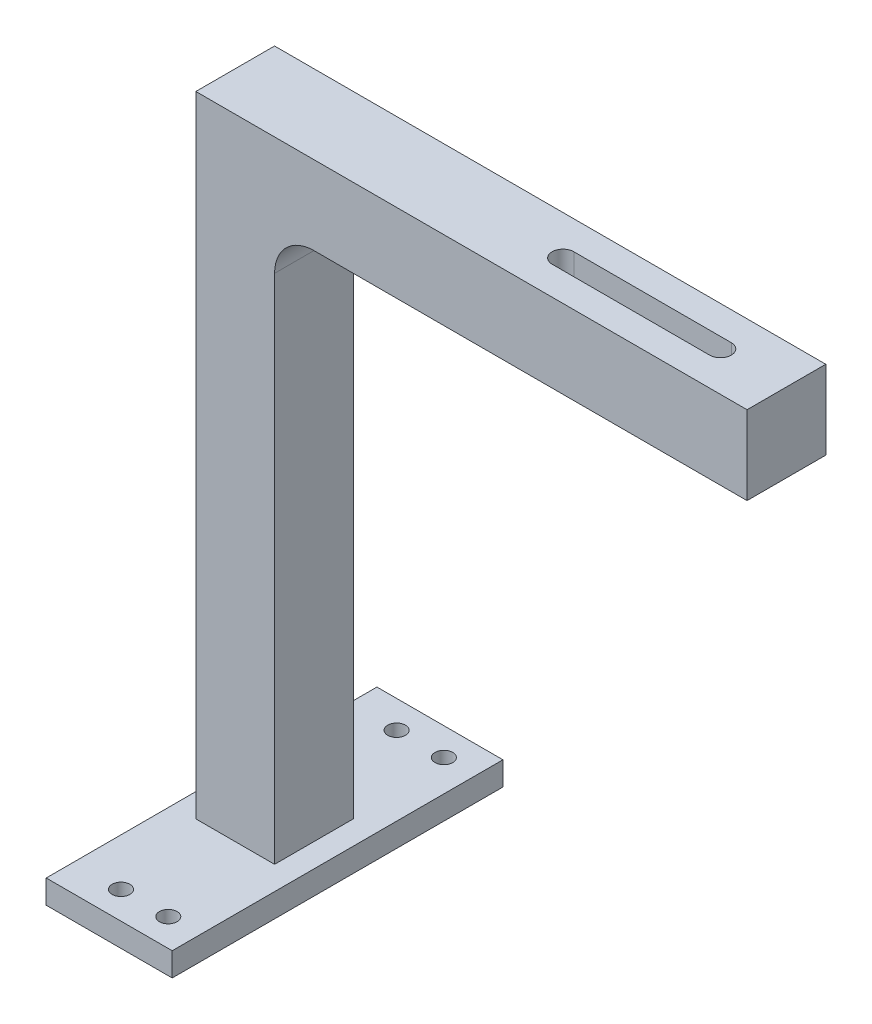
SolidWorks part; units mm, degrees
material "6061-T6 (SS)"
ref_plane "Front Plane" through (0, 0, 0) normal (0, 0, 1) x (1, 0, 0)
ref_plane "Top Plane" through (0, 0, 0) normal (0, 1, 0) x (1, 0, 0)
ref_plane "Right Plane" through (0, 0, 0) normal (1, 0, 0) x (0, 0, -1)
sketch "Sketch2" plane through (0, 0, 0) normal (0, 1, 0) x (1, 0, 0)
  line L1 (80, 42) -> (48, 42)
  line L2 (80, 42) -> (80, -42)
  line L3 (80, -42) -> (48, -42)
  line L4 (48, 42) -> (48, -42)
  line L5 (80, 42) -> (48, -42) construction
  line L6 (80, -42) -> (48, 42) construction
  point P0 (64, 0)
  point P5 (0, 0)
  dimension "D1" = 32
  dimension "D2" = 84
  dimension "D3" = 64
  dimension "D4" = 0
extrude "Stalk_Flange_32x84x6" add sketch "Sketch2" along normal blind 6
hole_wizard "Ø4.5 (4.5) Diameter Hole1" positions "Sketch3" profile "Sketch4" hole size "Ø4.5" standard "ISO" end condition through all
sketch "Sketch3" plane through (0, 6, 0) normal (0, 1, 0) x (1, 0, 0)
  point P0 (60, 35)
  point P2 (72, 35)
  point P4 (60, -35)
  point P6 (72, -35)
  dimension "D1" = 60
  dimension "D2" = 35
  dimension "D3" = 72
  dimension "D4" = 35
  dimension "D5" = 35
  dimension "D6" = 60
  dimension "D7" = 72
  dimension "D8" = 35
sketch "Sketch4" plane through (60, 6, -35) normal (1, 0, 0) x (0, 0, 1)
  line L0 (0, 0) -> (0, 6)
  line L1 (0, 6) -> (2.25, 6)
  line L2 (2.25, 6) -> (2.25, 0)
  line L5 (2.25, 0) -> (0, 0)
  line L11 (0, -6.35) -> (0, 107.95) construction
  dimension "Thru Hole Dia." = 4.5
  dimension "Thru Hole Depth" = 6
sketch "Sketch5" plane through (0, 6, 0) normal (0, 1, 0) x (1, 0, 0)
  line L1 (54, 10) -> (74, 10)
  line L2 (54, 10) -> (54, -10)
  line L3 (54, -10) -> (74, -10)
  line L4 (74, 10) -> (74, -10)
  line L5 (54, 10) -> (74, -10) construction
  line L6 (54, -10) -> (74, 10) construction
  point P0 (64, 0)
  dimension "D1" = 64
  dimension "D2" = 20
  dimension "D3" = 20
extrude "Vertical_Column_20x20x160" add sketch "Sketch5" along normal blind 160
sketch "Sketch6" plane through (0, 0, 0) normal (0, 0, 1) x (1, 0, 0)
  line L1 (74, 166) -> (194, 166)
  line L2 (74, 166) -> (74, 146)
  line L3 (74, 146) -> (194, 146)
  line L4 (194, 166) -> (194, 146)
  dimension "D1" = 120
  dimension "D2" = 20
extrude "Horizontal_Arm_20x20x120" add sketch "Sketch6" along normal mid plane 20
fillet "Inside_Fillet_R10" radius 10 1 edges at (74, 146, 0)
sketch "Sketch7" plane through (0, 166, 0) normal (0, 1, 0) x (1, 0, 0)
  line L0 (177.25, 0) -> (137.25, 0) construction
  line L1 (177.25, -2.75) -> (137.25, -2.75)
  line L2 (177.25, 2.75) -> (137.25, 2.75)
  line L5 (194, -10) -> (194, 10) construction
  arc A0 (177.25, -2.75) -> (177.25, 2.75) centre (177.25, 0) ccw
  arc A1 (137.25, 2.75) -> (137.25, -2.75) centre (137.25, 0) ccw
  point P3 (157.25, 0)
  point P8 (180, 0)
  dimension "D1" = 5.5
  dimension "D2" = 40
  dimension "D3" = 14
extrude "Tip_Slot_40x5.5_THRU" cut sketch "Sketch7" against normal through all
